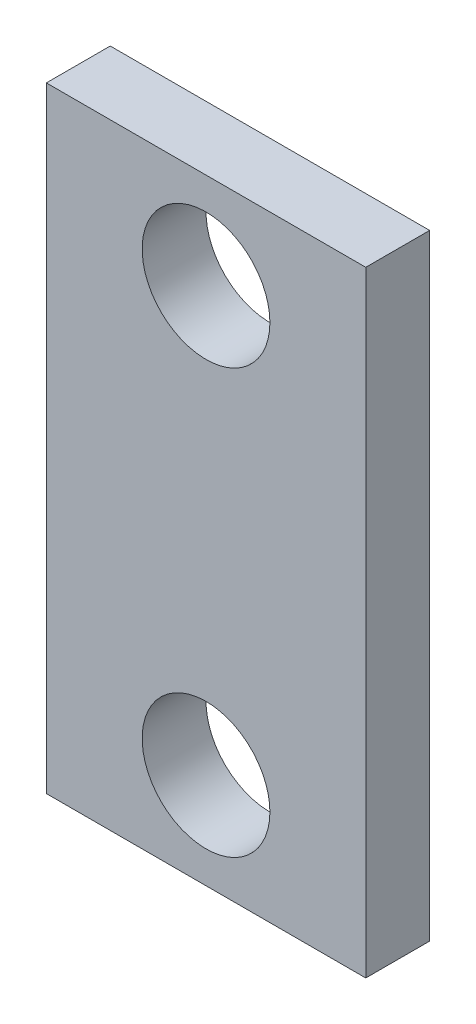
SolidWorks part; units mm, degrees
ref_plane "Ön Düzlem" through (0, 0, 0) normal (0, 0, 1) x (1, 0, 0)
ref_plane "Üst Düzlem" through (0, 0, 0) normal (0, 1, 0) x (1, 0, 0)
ref_plane "Sağ Düzlem" through (0, 0, 0) normal (1, 0, 0) x (0, 0, -1)
sketch "Çizim1" plane through (0, 0, 0) normal (0, 0, 1) x (1, 0, 0)
  line L4 (0, 0) -> (0, 19.27)
  line L5 (0, 19.27) -> (10, 19.27)
  line L6 (10, 19.27) -> (10, 0)
  line L7 (10, 0) -> (0, 0)
  circle A2 centre (4.9991, 16.27) radius 2
  circle A3 centre (4.9991, 3) radius 2
  dimension "D4" = 4
  dimension "D5" = 4
  dimension "D2" = 10
  dimension "D3" = 13.27
  dimension "D6" = 3
  dimension "D7" = 3
extrude "Yükseklik-Ekstrüzyon1" add sketch "Çizim1" along normal blind 2
